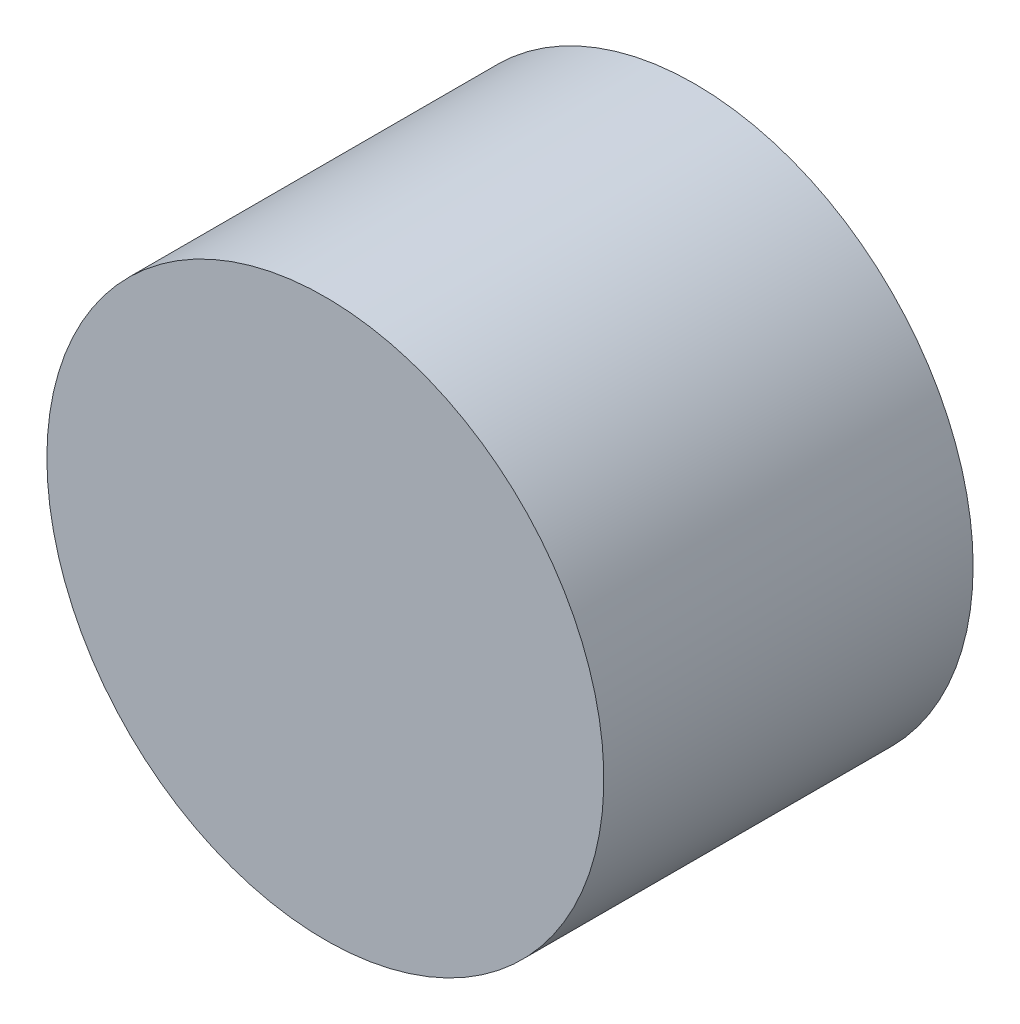
SolidWorks part; units mm, degrees
ref_plane "Front Plane" through (0, 0, 0) normal (0, 0, 1) x (1, 0, 0)
ref_plane "Top Plane" through (0, 0, 0) normal (0, 1, 0) x (1, 0, 0)
ref_plane "Right Plane" through (0, 0, 0) normal (1, 0, 0) x (0, 0, -1)
sketch "Sketch2" plane through (0, 0, 0) normal (0, 0, 1) x (1, 0, 0)
  circle A0 centre (-8.763, -27.305) radius 1.778
  dimension "D1" = 3.556
extrude "Boss-Extrude1" add sketch "Sketch2" against normal blind 1.651
sketch "Sketch4" plane through (0, 0, 0) normal (0, 0, 1) x (1, 0, 0)
  circle A0 centre (-8.763, -27.305) radius 4.4056
extrude "Boss-Extrude2" add sketch "Sketch4" along normal up to surface (5.842 mm away)
